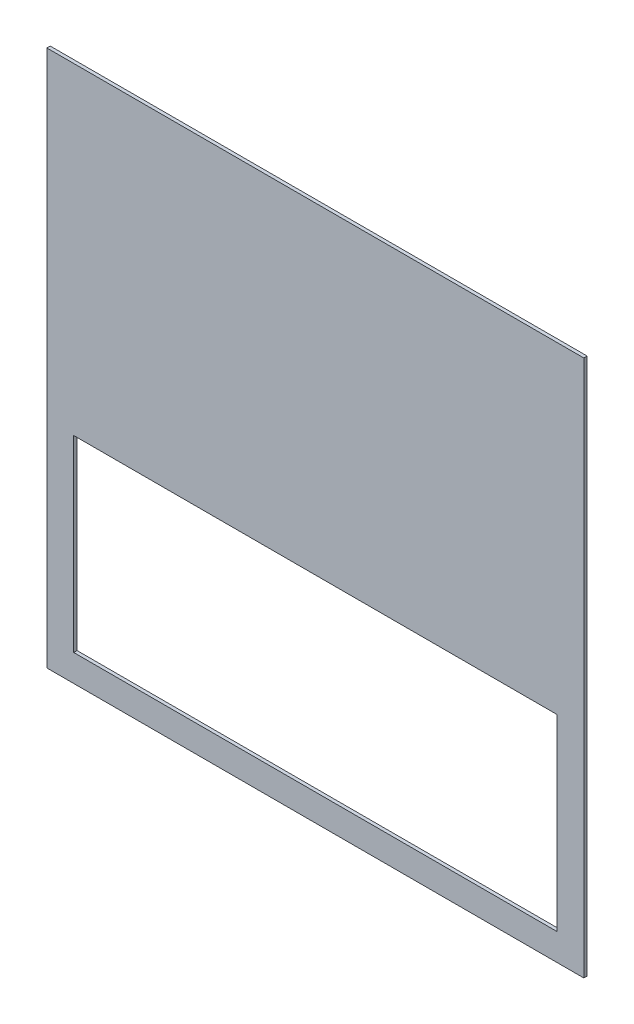
SolidWorks part; units mm, degrees
material "Acrylic (Medium-high impact)"
ref_plane "Front Plane" through (0, 0, 0) normal (0, 0, 1) x (1, 0, 0)
ref_plane "Top Plane" through (0, 0, 0) normal (0, 1, 0) x (1, 0, 0)
ref_plane "Right Plane" through (0, 0, 0) normal (1, 0, 0) x (0, 0, -1)
sketch "Sketch1" plane through (0, 0, 0) normal (0, 0, 1) x (1, 0, 0)
  line L1 (-254, -254) -> (254, -254)
  line L2 (-254, -254) -> (-254, 254)
  line L3 (-254, 254) -> (254, 254)
  line L4 (254, -254) -> (254, 254)
  line L5 (-254, -254) -> (254, 254) construction
  line L6 (-254, 254) -> (254, -254) construction
  point P0 (0, 0)
  dimension "D1" = 508
  dimension "D2" = 508
extrude "Boss-Extrude1" add sketch "Sketch1" along normal mid plane 3.175
sketch "Sketch2" plane through (0, 0, 1.5875) normal (0, 0, 1) x (1, 0, 0)
  line L0 (0, 177.8) -> (0, 0) construction
  line L1 (-228.6, 127) -> (228.6, 127)
  line L2 (-228.6, 127) -> (-228.6, 228.6)
  line L3 (-228.6, 228.6) -> (228.6, 228.6)
  line L4 (228.6, 127) -> (228.6, 228.6)
  line L5 (-228.6, 127) -> (228.6, 228.6) construction
  line L6 (-228.6, 228.6) -> (228.6, 127) construction
  line L8 (254, 254) -> (228.6, 254) construction
  line L9 (254, 254) -> (254, 228.6) construction
  line L10 (254, 228.6) -> (228.6, 228.6) construction
  line L11 (228.6, 254) -> (228.6, 228.6) construction
  point P0 (0, 177.8)
  dimension "D1" = 25.4
  dimension "D2" = 101.6
extrude "Cut-Extrude1" [suppressed] cut sketch "Sketch2" against normal through all
sketch "Sketch3" plane through (0, 0, -1.5875) normal (0, 0, -1) x (-1, 0, 0)
  line L0 (0, -139.7) -> (0, 0) construction
  line L1 (-228.6, -228.6) -> (228.6, -228.6)
  line L2 (-228.6, -228.6) -> (-228.6, -50.8)
  line L3 (-228.6, -50.8) -> (228.6, -50.8)
  line L4 (228.6, -228.6) -> (228.6, -50.8)
  line L5 (-228.6, -228.6) -> (228.6, -50.8) construction
  line L6 (-228.6, -50.8) -> (228.6, -228.6) construction
  line L12 (254, -254) -> (228.6, -254) construction
  line L13 (254, -254) -> (254, -228.6) construction
  line L14 (254, -228.6) -> (228.6, -228.6) construction
  line L15 (228.6, -254) -> (228.6, -228.6) construction
  point P0 (0, -139.7)
  dimension "D1" = 25.4
  dimension "D2" = 177.8
extrude "Cut-Extrude2" cut sketch "Sketch3" against normal through all
equation "\"D2@Sketch1\"=\"BOX SIZE\""
equation "\"D1@Sketch1\"=\"BOX SIZE\""
equation "\"BOX PLATE THK\"= .125"
equation "\"BOX SIZE\"= 20"
equation "\"STANDARD PROFILE\"= 1"
equation "\"D1@Boss-Extrude1\"= \"BOX PLATE THK\""
